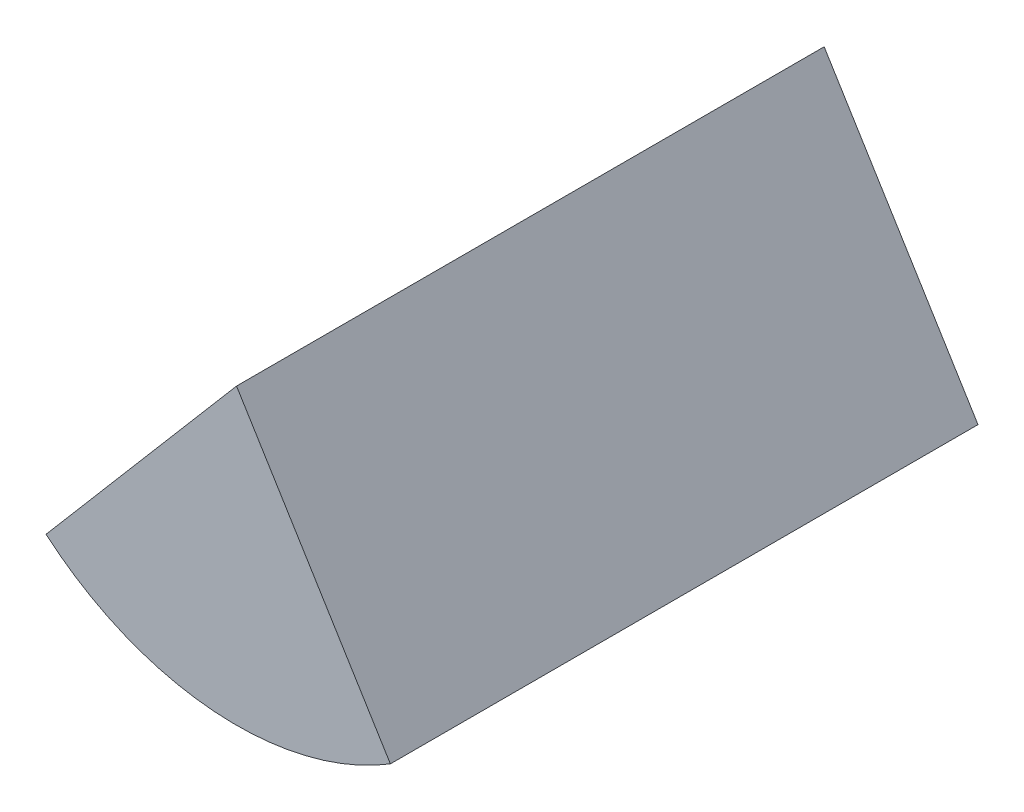
SolidWorks part; units mm, degrees
ref_plane "Alzado" through (0, 0, 0) normal (0, 0, 1) x (1, 0, 0)
ref_plane "Planta" through (0, 0, 0) normal (0, 1, 0) x (1, 0, 0)
ref_plane "Vista lateral" through (0, 0, 0) normal (1, 0, 0) x (0, 0, -1)
sketch "Croquis1" plane through (0, 0, 0) normal (0, 0, 1) x (1, 0, 0)
  line L1 (0, 0) -> (13.09, -21.2991)
  line L2 (0, 0) -> (-16.2116, -19.0311)
  arc A0 (-16.2116, -19.0311) -> (13.09, -21.2991) centre (0, 0) ccw
  dimension "D1" = 50
  dimension "D2" = 72
extrude "Saliente-Extruir1" add sketch "Croquis1" along normal blind 50
sketch "Croquis2" plane through (0, 0, 0) normal (0, 0, -1) x (-1, 0, 0)
  circle A0 centre (1.1775, -15.91) radius 5
  dimension "D1" = 10
extrude "Cortar-Extruir1" cut sketch "Croquis2" against normal blind 10
